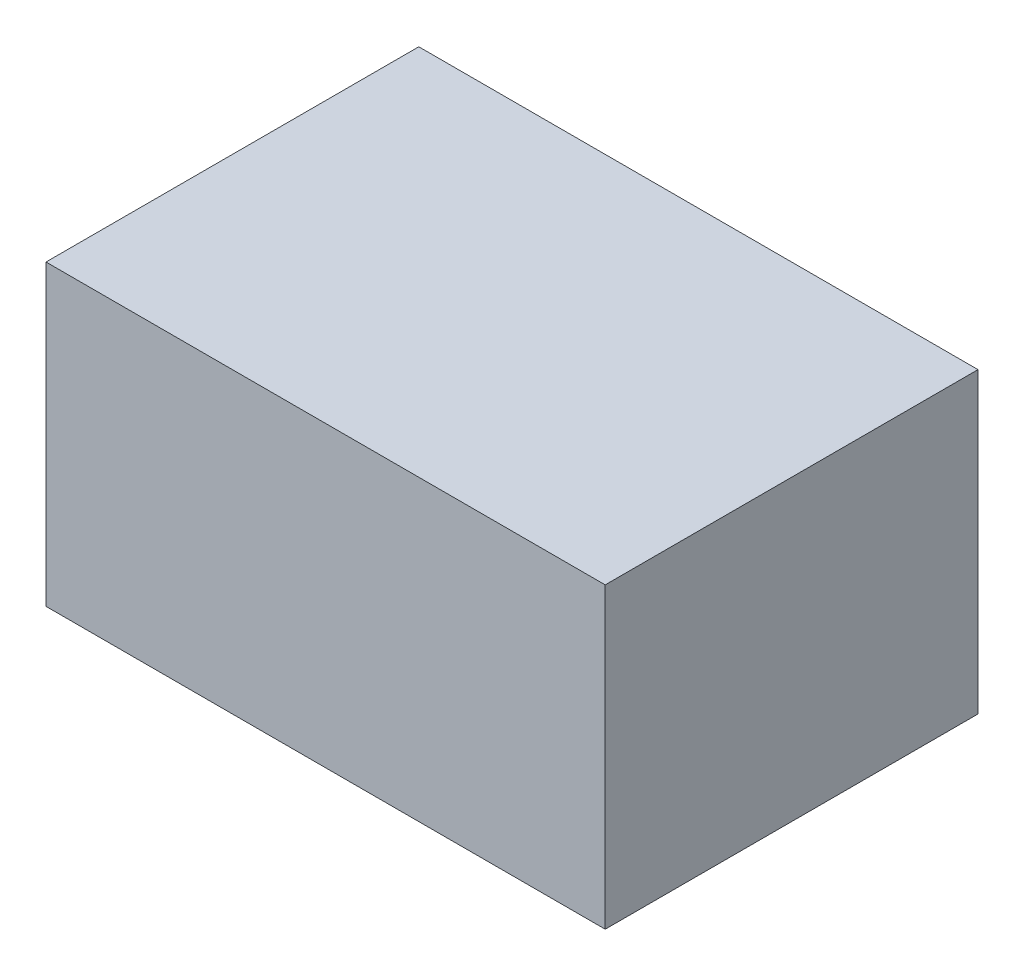
SolidWorks part; units mm, degrees
ref_plane "Front Plane" through (0, 0, 0) normal (0, 0, 1) x (1, 0, 0)
ref_plane "Top Plane" through (0, 0, 0) normal (0, 1, 0) x (1, 0, 0)
ref_plane "Right Plane" through (0, 0, 0) normal (1, 0, 0) x (0, 0, -1)
sketch "Sketch2" plane through (0, 0, 0) normal (0, 0, 1) x (1, 0, 0)
  line L1 (-75, 40) -> (75, 40)
  line L2 (-75, 40) -> (-75, -40)
  line L3 (-75, -40) -> (75, -40)
  line L4 (75, 40) -> (75, -40)
  line L5 (-75, 40) -> (75, -40) construction
  line L6 (-75, -40) -> (75, 40) construction
  point P0 (0, 0)
  dimension "D1" = 80
  dimension "D2" = 150
extrude "Boss-Extrude1" add sketch "Sketch2" against normal blind 100
sketch3d "3DSketch3"
  line L0 (72.5, -40, 0) -> (72.5, 40, 0)
  line L1 (72.5, -14.426, 0) -> (72.5, 40, 0)
  line L4 (62.5, -40, 0) -> (62.5, 40, 0)
  line L5 (62.5, -40, 0) -> (62.5, -25.054, 0)
  arc A0 (62.5, -25.054, 0) -> (67.4899, -20.1576, 0) centre (67.3973, -25.054, 0) cw
  arc A1 (67.4899, -20.1576, 0) -> (72.47, -15.0143, 0) centre (66.7165, -14.426, 0) cw
  point P3 (0, 0, 0)
  point P20 (67.3973, -25.054, -4.8973)
  point P23 (66.7165, -14.426, 5.7835)
  point P24 (67.5, -20.1638, 0)
  dimension "D1" = 2.5
  dimension "D3" = 12.5
